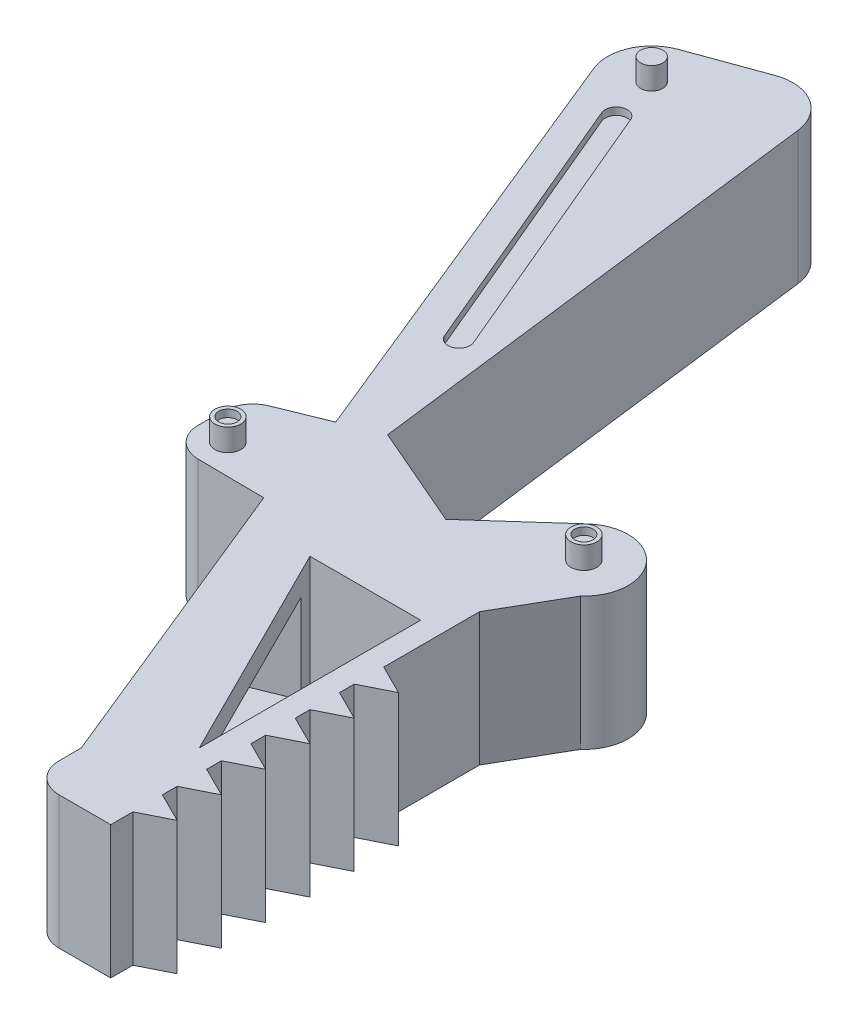
SolidWorks part; units mm, degrees
ref_plane "Front Plane" through (0, 0, 0) normal (0, 0, 1) x (1, 0, 0)
ref_plane "Top Plane" through (0, 0, 0) normal (0, 1, 0) x (1, 0, 0)
ref_plane "Right Plane" through (0, 0, 0) normal (1, 0, 0) x (0, 0, -1)
sketch "Sketch2" plane through (0, 0, 0) normal (0, 1, 0) x (1, 0, 0)
  line L0 (0, 0) -> (-160.4074, 0) construction
  line L1 (-22, -73.0367) -> (-48.4066, -8.2085)
  line L2 (-48.4066, -8.2085) -> (-25.854, 0)
  line L3 (-25.854, 0) -> (-17, -71)
  line L4 (-17, -71) -> (-22, -73.0367)
  line L5 (-17, -71) -> (-30.8918, -76.6586)
  line L6 (-30.8918, -76.6586) -> (-30.9992, -86.658)
  line L7 (-30.9992, -86.658) -> (-18, -86.7977)
  line L8 (-18, -86.7977) -> (-1, -128.5327)
  line L9 (-1, -128.5327) -> (-1, -135.5327)
  line L10 (-1, -135.5327) -> (10, -135.5327)
  line L11 (10, -135.5327) -> (10, -85.5327)
  line L12 (10, -85.5327) -> (15, -76.8725)
  line L13 (-17, -71) -> (-3.1342, -76.9925)
  line L14 (-3.1342, -76.9925) -> (7, -67.9282)
  arc A0 (7, -67.9282) -> (15, -76.8725) centre (11, -72.4003) cw
  dimension "D12" = 6
  dimension "D1" = 70
  dimension "D2" = 71
  dimension "D3" = 24
  dimension "D4" = 15
  dimension "D5" = 10
  dimension "D6" = 13
  dimension "D7" = 20
  dimension "D8" = 7
  dimension "D9" = 11
  dimension "D10" = 50
  dimension "D11" = 10
  dimension "D15" = 7
  dimension "D16" = 10
  dimension "D17" = 11
  dimension "D18" = 15
  dimension "D20" = 17
  dimension "D21" = 18
  dimension "D22" = 22
extrude "Boss-Extrude1" add sketch "Sketch2" along normal mid plane 18 contours A0 L14 L13 L5 L6 L7 L8 L9 L10 L11 L12 | L4 L3 L2 L1
fillet "Fillet1" radius 6 2 edges at (-25.854, 0, 0) (-48.4066, 0, 8.2085)
fillet "Fillet2" radius 4 3 edges at (-1, 0, 135.5327) (-30.9992, 0, 86.658) (-30.8918, 0, 76.6586)
sketch "Sketch3" plane through (0, 9, 0) normal (0, 1, 0) x (1, 0, 0)
  line L0 (10, -135.5327) -> (10, -130.5327) construction
  line L1 (10, -135.5327) -> (10, -85.5327) construction
  line L2 (10, -130.5327) -> (14, -130.5327) construction
  line L3 (10, -132.5327) -> (10, -128.5327)
  line L4 (10, -128.5327) -> (14, -130.5327)
  line L5 (10, -132.5327) -> (14, -130.5327)
  point P9 (10, -130.5327)
  dimension "D1" = 5
  dimension "D2" = 4
  dimension "D3" = 4
extrude "Boss-Extrude2" add sketch "Sketch3" against normal blind 18
pattern_linear "LPattern1" count 6 spacing 6 along (0, 0, -1) of "Boss-Extrude2"
sketch "Sketch5" plane through (0, 9, 0) normal (0, 1, 0) x (1, 0, 0)
  line L0 (7, -120.5327) -> (7, -90.5327)
  line L1 (7, -90.5327) -> (-8, -90.5327)
  line L2 (-8, -90.5327) -> (7, -120.5327)
  line L3 (-1, -128.5327) -> (-1, -131.5327) construction
  line L4 (3, -135.5327) -> (10, -135.5327) construction
  dimension "D1" = 15
  dimension "D2" = 30
  dimension "D3" = 8
  dimension "D4" = 15
extrude "Cut-Extrude1" cut sketch "Sketch5" against normal through all
sketch "Sketch6" plane through (-45.7626, 0, 18.6406) normal (-0.9261, 0, 0.3772) x (0.3772, 0, 0.9261)
  line L0 (83.5946, 6) -> (83.5946, -6)
  line L1 (83.5946, -6) -> (113.6591, -6)
  line L2 (113.6591, -6) -> (113.6591, 6)
  line L3 (113.6591, 6) -> (83.5946, 6)
  line L4 (73.5946, 9) -> (73.5946, -9) construction
  line L5 (73.5946, 9) -> (118.6591, 9) construction
  line L6 (118.6591, 9) -> (118.6591, -9) construction
  point P6 (73.5946, 0)
  point P7 (83.5946, 0)
  point P8 (113.6591, 0)
  dimension "D1" = 3
  dimension "D2" = 5
  dimension "D3" = 10
  dimension "D4" = 12
extrude "Cut-Extrude2" cut sketch "Sketch6" against normal blind 10
sketch "Sketch8" plane through (0, 9, 0) normal (0, 1, 0) x (1, 0, 0)
  circle A0 centre (-26.9565, -82.7012) radius 1.75
  circle A1 centre (11, -72.4003) radius 1.75
  circle A2 centre (-40.4994, -11.7156) radius 1.5
  dimension "D1" = 3.5
  dimension "D2" = 3.5
  dimension "D3" = 3
extrude "Boss-Extrude3" add sketch "Sketch8" along normal blind 3
sketch "Sketch9" plane through (0, 12, 0) normal (0, 1, 0) x (1, 0, 0)
  circle A2 centre (-26.9565, -82.7012) radius 1.25
  circle A3 centre (-26.9565, -82.7012) radius 1.25
  dimension "D1" = 0.5
extrude "Cut-Extrude4" cut sketch "Sketch9" against normal blind 1
sketch "Sketch10" plane through (0, 12, 0) normal (0, 1, 0) x (1, 0, 0)
  circle A2 centre (11, -72.4003) radius 1.25
  circle A3 centre (11, -72.4003) radius 1.25
  dimension "D1" = 0.5
extrude "Cut-Extrude5" cut sketch "Sketch10" against normal blind 1
sketch "Sketch11" plane through (0, 9, 0) normal (0, 1, 0) x (1, 0, 0)
  line L0 (-38.9255, -18.0933) -> (-23.3821, -54.9499) construction
  line L1 (-37.5434, -17.5104) -> (-22, -54.367)
  line L2 (-40.3076, -18.6762) -> (-24.7642, -55.5327)
  line L3 (10, -135.5327) -> (10, -132.5327) construction
  line L5 (-27.7461, -3.0942) -> (-26.0626, -36.7159) construction
  arc A0 (-37.5434, -17.5104) -> (-40.3076, -18.6762) centre (-38.9255, -18.0933) ccw
  arc A1 (-24.7642, -55.5327) -> (-22, -54.367) centre (-23.3821, -54.9499) ccw
  arc A2 (-24.9224, -7.4706) -> (-32.9284, -2.5749) centre (-30.8762, -8.213) ccw construction
  point P2 (-31.1538, -36.5216)
  dimension "D1" = 1.5
  dimension "D2" = 40
  dimension "D3" = 20
  dimension "D4" = 32
  dimension "D5" = 65
extrude "Cut-Extrude6" cut sketch "Sketch11" against normal blind 1
mirror "Mirror1" about plane through (0, 0, 0) normal (0, 1, 0) of "Cut-Extrude6", "Cut-Extrude5", "Cut-Extrude4", "Boss-Extrude3"
